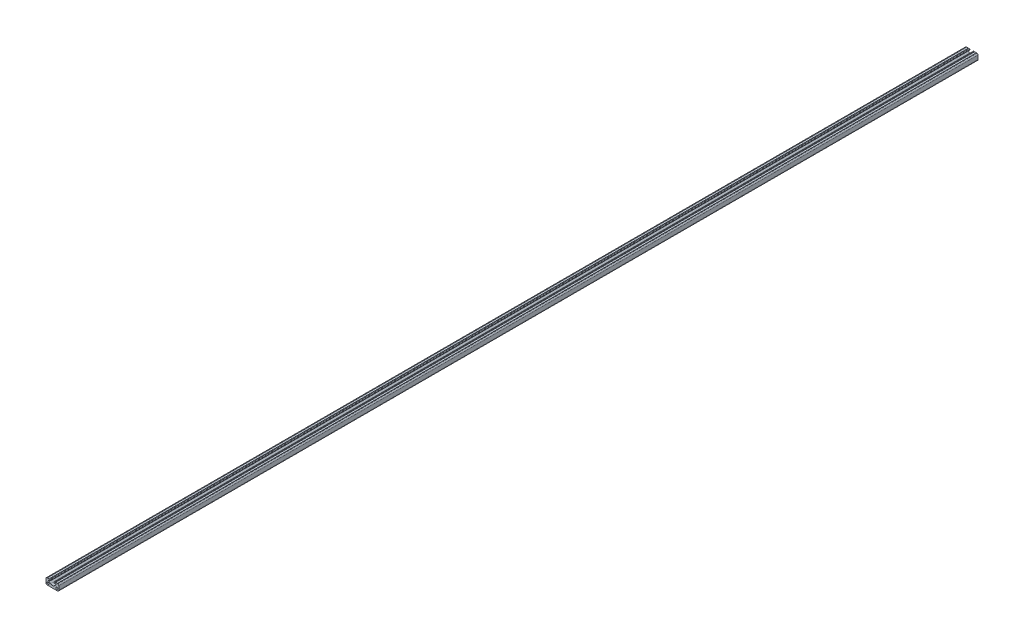
SolidWorks part; units mm, degrees
ref_plane "Front Plane" through (0, 0, 0) normal (0, 0, 1) x (1, 0, 0)
ref_plane "Top Plane" through (0, 0, 0) normal (0, 1, 0) x (1, 0, 0)
ref_plane "Right Plane" through (0, 0, 0) normal (1, 0, 0) x (0, 0, -1)
sketch "Sketch1" plane through (0, 0, 0) normal (0, 0, 1) x (1, 0, 0)
  line L0 (0, 6.35) -> (0, -6.35) construction
  line L1 (0, -6.35) -> (12.7, -6.35)
  line L2 (12.7, -6.35) -> (12.7, 6.35)
  line L3 (12.7, 6.35) -> (3.2512, 6.35)
  line L4 (3.2512, 6.35) -> (3.2512, 4.1402)
  line L5 (3.2512, 4.1402) -> (6.4224, 4.1402)
  line L6 (7.1255, 2.4426) -> (2.9811, -1.7018)
  line L7 (2.9811, -1.7018) -> (0, -1.7018)
  circle A0 centre (8.7249, -2.3876) radius 2.032
  arc A1 (6.4224, 4.1402) -> (7.1255, 2.4426) centre (6.4224, 3.1458) cw
  dimension "Center Hole Diameter" = 4.064
  dimension "D3" = 0.9944
  dimension "Rail Height" = 25.4
  dimension "Rail Width" = 12.7
  dimension "Hole CtoC" = 17.4498
  dimension "D1" = 3.9624
  dimension "T-Slot Width" = 6.5024
  dimension "Thickness" = 2.2098
  dimension "Inner Slot Width" = 14.8336
  dimension "Slot Depth" = 5.842
  dimension "D2" = 45
sketch "Sketch2" plane through (0, 0, 0) normal (1, 0, 0) x (0, 0, -1)
  line L0 (-914.4, -6.35) -> (914.4, -6.35) construction
  line L1 (-889, 0) -> (889, 0) construction
  dimension "Length" = 1828.8
  dimension "D1" = 25.4
sketch "Sketch3" plane through (0, 0, 0) normal (0, 0, 1) x (1, 0, 0)
  line L0 (3.2512, 6.35) -> (3.2512, 4.1402) construction
  line L1 (12.7, 6.35) -> (3.2512, 6.35) construction
  line L2 (3.2512, 4.1402) -> (6.4224, 4.1402) construction
  line L3 (3.2512, 5.3556) -> (3.2512, 5.1346)
  line L4 (12.7, -6.35) -> (12.7, 6.35) construction
  line L5 (0, -6.35) -> (12.7, -6.35) construction
  line L6 (2.9811, -1.7018) -> (0, -1.7018) construction
  line L7 (7.1255, 2.4426) -> (2.9811, -1.7018) construction
  line L8 (0, -1.7018) -> (1.7454, -1.7018)
  line L9 (4.2456, 4.1402) -> (6.4224, 4.1402)
  line L10 (3.8549, -0.828) -> (7.1255, 2.4426)
  line L11 (0, -1.7018) -> (0, -6.35)
  line L12 (0, -6.35) -> (10.16, -6.35)
  line L13 (12.7, -3.81) -> (12.7, 3.81)
  line L14 (4.2456, 6.35) -> (10.16, 6.35)
  arc A0 (3.2512, 5.3556) -> (4.2456, 6.35) centre (4.2456, 5.3556) cw
  arc A1 (3.2512, 5.1346) -> (4.2456, 4.1402) centre (4.2456, 5.1346) ccw
  arc A2 (7.1255, 2.4426) -> (6.4224, 4.1402) centre (6.4224, 3.1458) ccw construction
  arc A3 (10.16, 6.35) -> (12.7, 3.81) centre (10.16, 3.81) cw
  arc A4 (10.16, -6.35) -> (12.7, -3.81) centre (10.16, -3.81) ccw
  arc A5 (7.1255, 2.4426) -> (6.4224, 4.1402) centre (6.4224, 3.1458) ccw
  circle A6 centre (8.7249, -2.3876) radius 2.032 construction
  circle A7 centre (8.7249, -2.3876) radius 2.032
  arc A8 (1.7454, -1.7018) -> (3.8549, -0.828) centre (1.7454, 1.2814) ccw
  dimension "D2" = 2.9832
  dimension "D1" = 2.54
extrude "Boss-Extrude1" add sketch "Sketch3" along normal mid plane 1828.8
sketch "Sketch4" plane through (0, 0, 0) normal (0, 0, 1) x (1, 0, 0)
  line L0 (12.7, 6.35) -> (3.2512, 6.35) construction
  line L1 (0, -6.35) -> (12.7, -6.35) construction
  line L2 (10.7569, -2.3876) -> (10.7569, 6.35) construction
  line L3 (6.4224, 3.1458) -> (6.4224, 6.35) construction
  circle A0 centre (5.8699, 6.35) radius 0.5524
  circle A1 centre (10.2045, 6.35) radius 0.5524
  circle A2 centre (5.8699, -6.35) radius 0.5524
  circle A3 centre (10.2045, -6.35) radius 0.5524
  circle A4 centre (8.7249, -2.3876) radius 2.032 construction
  dimension "D1" = 1.1049
extrude "Cut-Extrude1" cut sketch "Sketch4" against normal through all both and the other way through all
mirror "Mirror1" about plane through (0, 0, 0) normal (1, 0, 0) of bodies 135
equation "\"D3@Sketch1\"=\"Thickness@Sketch1\"*0.45"
equation "\"D1@Sketch3\"=\"Rail Width@Sketch1\"*0.2"
equation "\"D2@Sketch3\"=\"D3@Sketch1\"*3"
equation "\"D1@Boss-Extrude1\"=\"length@sketch2\""
equation "\"D1@Sketch4\"=\"Thickness@Sketch1\"*0.5"
